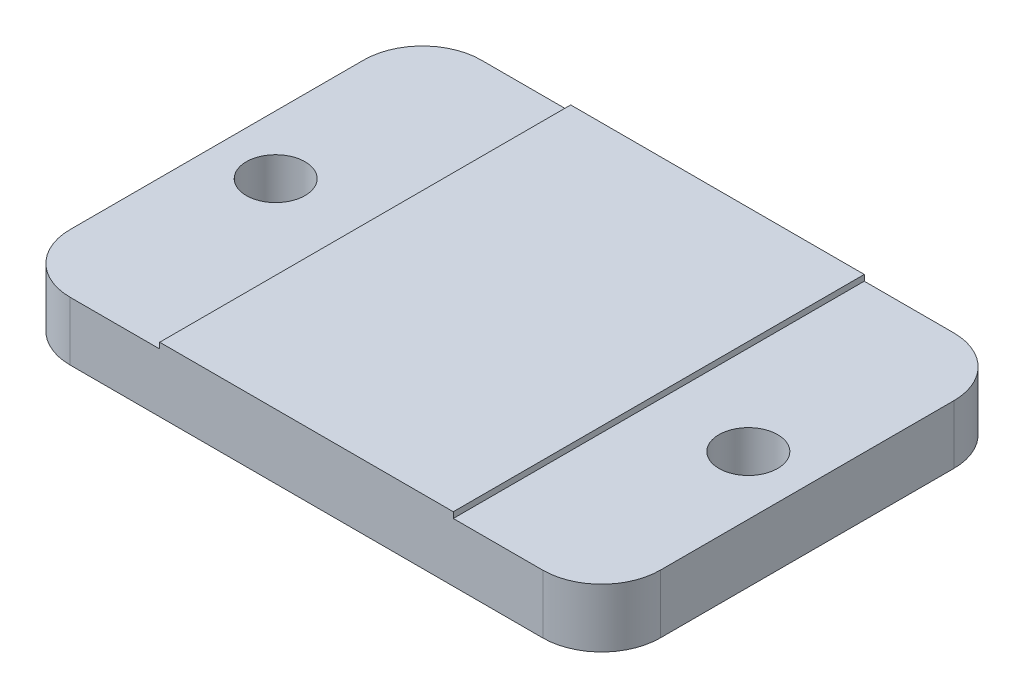
SolidWorks part; units mm, degrees
ref_plane "前视基准面" through (0, 0, 0) normal (0, 0, 1) x (1, 0, 0)
ref_plane "上视基准面" through (0, 0, 0) normal (0, 1, 0) x (1, 0, 0)
ref_plane "右视基准面" through (0, 0, 0) normal (1, 0, 0) x (0, 0, -1)
sketch "草图1" plane through (0, 0, 0) normal (0, 1, 0) x (1, 0, 0)
  line L0 (0, 15.343) -> (0, -12.395) construction
  line L1 (-10.05, 7) -> (10.05, 7)
  line L2 (-10.05, 7) -> (-10.05, -7)
  line L3 (-10.05, -7) -> (10.05, -7)
  line L4 (10.05, 7) -> (10.05, -7)
  line L5 (-10.05, 7) -> (10.05, -7) construction
  line L6 (-10.05, -7) -> (10.05, 7) construction
  line L7 (0, 0) -> (-8.05, 0) construction
  circle A0 centre (-8.05, 0) radius 1
  circle A1 centre (8.05, 0) radius 1
  point P0 (0, 0)
  dimension "D3" = 2
  dimension "D1" = 20.1
  dimension "D2" = 14
  dimension "D4" = 2
extrude "凸台-拉伸1" add sketch "草图1" along normal blind 2
sketch "草图2" plane through (0, 2, 0) normal (0, 1, 0) x (1, 0, 0)
  line L0 (-10.05, -7) -> (10.05, -7) construction
  line L1 (-5, 7) -> (5, 7)
  line L2 (-5, 7) -> (-5, -7)
  line L3 (-5, -7) -> (5, -7)
  line L4 (5, 7) -> (5, -7)
  line L5 (-5, 7) -> (5, -7) construction
  line L6 (-5, -7) -> (5, 7) construction
  point P0 (0, 0)
  dimension "D1" = 10
extrude "凸台-拉伸2" add sketch "草图2" along normal blind 0.2
fillet "圆角1" radius 2 4 edges at (-10.05, 1, 7) (-10.05, 1, -7) (10.05, 1, 7) (10.05, 1, -7)
